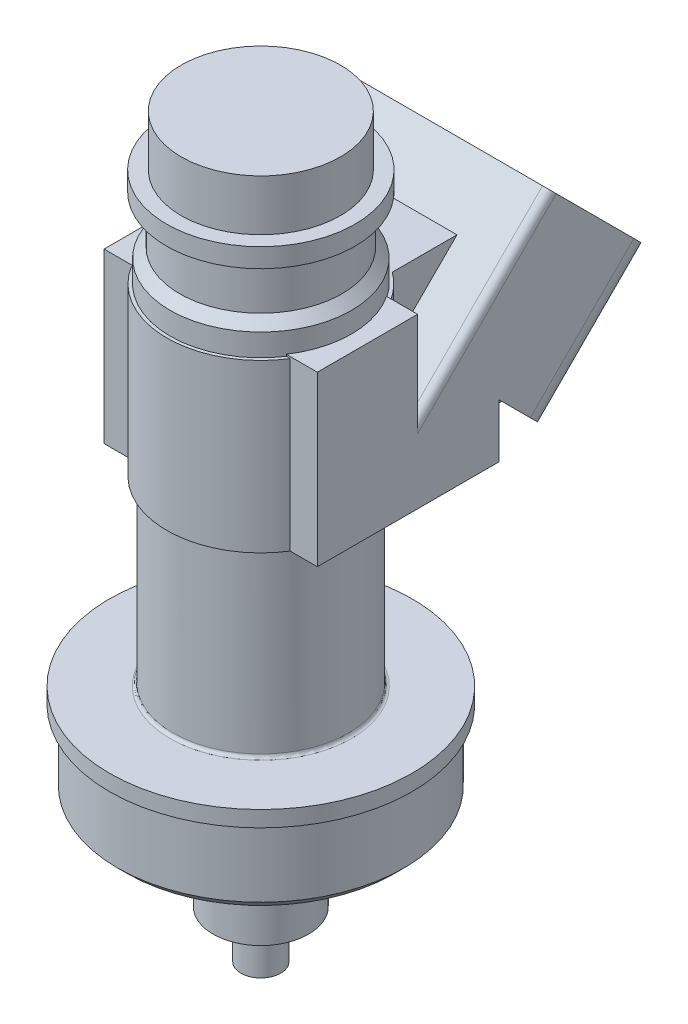
SolidWorks part; units mm, degrees
ref_plane "Front" through (0, 0, 0) normal (0, 0, 1) x (1, 0, 0)
ref_plane "Top" through (0, 0, 0) normal (0, 1, 0) x (1, 0, 0)
ref_plane "Right" through (0, 0, 0) normal (1, 0, 0) x (0, 0, -1)
sketch "Sketch1" plane through (0, 0, 0) normal (0, 1, 0) x (1, 0, 0)
  circle A0 centre (0, 0) radius 1.5875
  dimension "D1" = 3.175
extrude "Extrude1" add sketch "Sketch1" along normal blind 3.81
sketch "Sketch2" plane through (0, 3.81, 0) normal (0, 1, 0) x (1, 0, 0)
  circle A0 centre (0, 0) radius 3.81
  dimension "D1" = 7.62
extrude "Extrude2" add sketch "Sketch2" along normal blind 7.62
sketch "Sketch3" plane through (0, 11.43, 0) normal (0, 1, 0) x (1, 0, 0)
  circle A0 centre (0, 0) radius 11.43
  dimension "D1" = 22.86
extrude "Extrude3" add sketch "Sketch3" along normal blind 6.35
sketch "Sketch4" plane through (0, 17.78, 0) normal (0, 1, 0) x (1, 0, 0)
  circle A0 centre (0, 0) radius 12.065
  dimension "D1" = 24.13
extrude "Extrude4" add sketch "Sketch4" along normal blind 1.27
sketch "Sketch5" plane through (0, 19.05, 0) normal (0, 1, 0) x (1, 0, 0)
  circle A0 centre (0, 0) radius 7
  dimension "D1" = 14
extrude "Extrude5" add sketch "Sketch5" along normal blind 14.5
sketch "Sketch6" plane through (0, 33.55, 0) normal (0, 1, 0) x (1, 0, 0)
  circle A0 centre (0, 0) radius 7.5
  dimension "D1" = 15
extrude "Extrude6" add sketch "Sketch6" along normal blind 13.3
sketch "Sketch7" plane through (0, 46.85, 0) normal (0, 1, 0) x (1, 0, 0)
  circle A0 centre (0, 0) radius 7.239
  dimension "D1" = 14.478
extrude "Extrude7" add sketch "Sketch7" along normal blind 2.54
chamfer "Chamfer6" distance 0.762 angle 45 1 edges at (0, 49.39, 7.239)
sketch "Sketch8" plane through (0, 49.39, 0) normal (0, 1, 0) x (1, 0, 0)
  circle A0 centre (0, 0) radius 6.477
  circle A1 centre (0, 0) radius 6.477 construction
extrude "Extrude8" add sketch "Sketch8" along normal blind 3.81
sketch "Sketch9" plane through (0, 0, 0) normal (0, -1, 0) x (1, 0, 0)
  circle A0 centre (0, 0) radius 0.7937
  dimension "D1" = 1.5875
extrude "Cut-Extrude1" cut sketch "Sketch9" against normal blind 2.54
chamfer "Chamfer1" distance 1.27 angle 20 1 edges at (0, 0, -0.7937)
sketch "Sketch10" plane through (0, 53.2, 0) normal (0, 1, 0) x (1, 0, 0)
  circle A0 centre (0, 0) radius 7.5185
extrude "Extrude9" add sketch "Sketch10" along normal blind 1.524
sketch "Sketch11" plane through (0, 54.724, 0) normal (0, 1, 0) x (1, 0, 0)
  circle A0 centre (0, 0) radius 6.35
  dimension "D1" = 12.7
extrude "Extrude10" add sketch "Sketch11" along normal blind 4.064
fillet "Fillet1" radius 0.254 1 edges at (0, 19.05, 7)
chamfer "Chamfer7" distance 0.762 angle 45 1 edges at (0, 11.43, 11.43)
sketch "Sketch12" plane through (0, 0, 0) normal (1, 0, 0) x (0, 0, -1)
  line L0 (-4.0005, 33.55) -> (-4.0005, 46.9935)
  line L1 (-7, 33.55) -> (7, 33.55) construction
  line L2 (-4.0005, 46.9935) -> (4.0005, 46.9935)
  line L3 (4.0005, 46.9935) -> (4.0005, 39.6454)
  line L4 (4.0005, 39.6454) -> (14.6084, 50.2533)
  line L5 (14.6084, 50.2533) -> (23.0499, 41.8118)
  line L6 (23.0499, 41.8118) -> (14.788, 33.55)
  line L7 (14.788, 33.55) -> (10.4775, 37.8605)
  line L8 (10.4775, 37.8605) -> (10.4775, 33.55)
  line L9 (10.4775, 33.55) -> (-4.0005, 33.55)
  line L10 (0, 0) -> (0, 46.9935) construction
  dimension "D1" = 14.478
  dimension "D2" = 11.684
  dimension "D3" = 11.938
  dimension "D4" = 8.001
  dimension "D5" = 5.842
extrude "Extrude11" add sketch "Sketch12" along normal mid plane 17.018
sketch "Sketch13" plane through (0, 32.4308, -32.4308) normal (0, 0.7071, -0.7071) x (1, 0, 0)
  line L12 (-6.985, -14.7907) -> (-6.985, -23.6807)
  line L13 (-6.985, -23.6807) -> (6.985, -23.6807)
  line L14 (6.985, -23.6807) -> (6.985, -14.7907)
  line L15 (6.985, -14.7907) -> (-6.985, -14.7907)
  line L16 (-6.985, -14.7907) -> (-6.985, -23.6807)
  line L17 (-6.985, -23.6807) -> (6.985, -23.6807)
  line L18 (6.985, -23.6807) -> (6.985, -14.7907)
  line L19 (6.985, -14.7907) -> (-6.985, -14.7907)
  dimension "D1" = 1.524
extrude "Cut-Extrude2" cut sketch "Sketch13" against normal offset from surface (10.414 mm away) 1.27 up to face at (0, 35.7053, -12.6328)
sketch "Sketch14" plane through (0, 25.067, -25.067) normal (0, 0.7071, -0.7071) x (1, 0, 0)
  line L1 (-4.7611, -23.6596) -> (-1.9977, -23.6596)
  line L2 (-4.7611, -23.6596) -> (-4.7611, -24.7426)
  line L3 (-4.7611, -24.7426) -> (-1.9977, -24.7426)
  line L4 (-1.9977, -23.6596) -> (-1.9977, -24.7426)
  line L5 (0.579, -23.6596) -> (3.6039, -23.6596)
  line L6 (0.579, -23.6596) -> (0.579, -24.7426)
  line L7 (0.579, -24.7426) -> (3.6039, -24.7426)
  line L8 (3.6039, -23.6596) -> (3.6039, -24.7426)
extrude "Extrude12" add sketch "Sketch14" along normal blind 6.35
chamfer "Chamfer8" distance 0.762 angle 45 4 edges at (-4.7611, 46.2945, -12.8198) (-1.9977, 46.2945, -12.8198) (0.579, 46.2945, -12.8198) (3.6039, 46.2945, -12.8198)
fillet "Fillet2" radius 2.54 6 edges at (-8.509, 37.6809, -18.9189) (8.509, 37.6809, -18.9189) (6.985, 39.2076, -18.2903) (-6.985, 39.2076, -18.2903) (-6.985, 45.4937, -12.0041) (6.985, 45.4937, -12.0041)
fillet "Fillet3" radius 0.635 2 edges at (8.509, 44.9493, -9.3045) (-8.509, 44.9493, -9.3045)
sketch "Sketch15" plane through (0, 0, 0) normal (1, 0, 0) x (0, 0, -1)
  line L0 (5.3602, 46.85) -> (12.1032, 46.85)
  line L1 (7.239, 46.85) -> (-7.239, 46.85) construction
  line L3 (15.0574, 49.8043) -> (4.0005, 38.7473) construction
  line L4 (12.1032, 46.85) -> (5.3602, 41.005)
  line L6 (4.0005, 39.6454) -> (14.6084, 50.2533) construction
  line L7 (5.3602, 41.005) -> (5.3602, 46.85)
  line L8 (10.4775, 33.55) -> (14.788, 33.55)
  line L9 (-4.0005, 33.55) -> (10.4775, 33.55) construction
  line L10 (14.788, 33.55) -> (10.4775, 37.8605)
  line L11 (10.4775, 37.8605) -> (10.4775, 33.55)
extrude "Extrude13" add sketch "Sketch15" along normal mid plane 8.89
